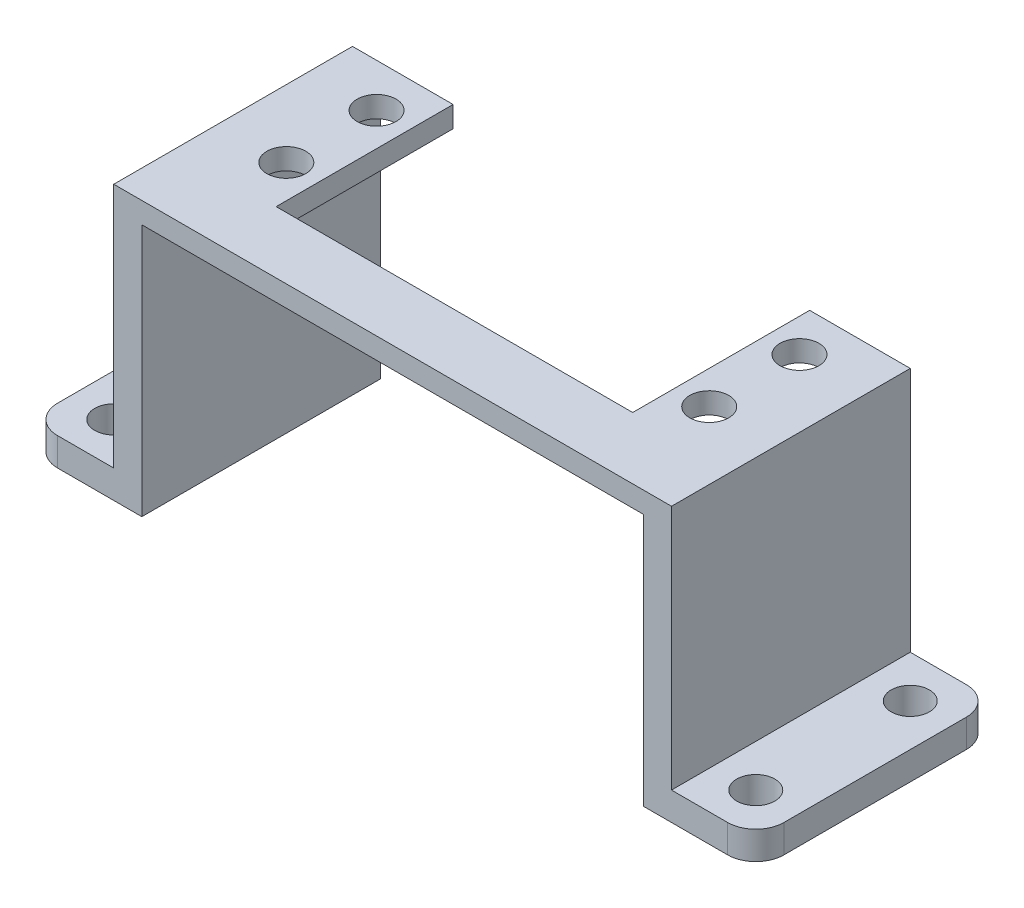
SolidWorks part; units mm, degrees
ref_plane "Front Plane" through (0, 0, 0) normal (0, 0, 1) x (1, 0, 0)
ref_plane "Top Plane" through (0, 0, 0) normal (0, 1, 0) x (1, 0, 0)
ref_plane "Right Plane" through (0, 0, 0) normal (1, 0, 0) x (0, 0, -1)
sketch "Sketch1" plane through (0, 0, 0) normal (0, 1, 0) x (1, 0, 0)
  line L0 (20.15, 0) -> (-20.15, 0)
  line L1 (-20.15, 0) -> (-20.15, 20)
  line L2 (-20.15, 20) -> (-31.52, 20)
  line L3 (-31.52, 20) -> (-31.52, -6.985)
  line L4 (-31.52, -6.985) -> (31.52, -6.985)
  line L5 (0, 0) -> (0, -6.985)
  line L6 (31.52, 20) -> (31.52, -6.985)
  line L7 (20.15, 20) -> (31.52, 20)
  line L8 (20.15, 0) -> (20.15, 20)
  circle A0 centre (-23.9, 15.1) radius 2.2
  circle A1 centre (-23.9, 4.9) radius 2.2
  circle A2 centre (23.9, 4.9) radius 2.2
  circle A3 centre (23.9, 15.1) radius 2.2
  point P0 (0, 0)
  dimension "D3" = 4.4
  dimension "D6" = 4.4
  dimension "D1" = 3.75
  dimension "D2" = 7.62
  dimension "D4" = 4.9
  dimension "D5" = 10.2
  dimension "D7" = 4.9
  dimension "D8" = 6.985
  dimension "D9" = 23.9
  dimension "D10" = 0
extrude "Boss-Extrude1" add sketch "Sketch1" along normal blind 2.3813
sketch "Sketch2" plane through (0, 0, 0) normal (0, -1, 0) x (1, 0, 0)
  line L0 (-31.52, 6.985) -> (31.52, 6.985) construction
  line L1 (31.52, -20) -> (28.345, -20)
  line L2 (31.52, -20) -> (31.52, 6.985)
  line L3 (31.52, 6.985) -> (28.345, 6.985)
  line L4 (28.345, -20) -> (28.345, 6.985)
  line L6 (-31.52, -20) -> (-28.345, -20)
  line L7 (-31.52, -20) -> (-31.52, 6.985)
  line L8 (-31.52, 6.985) -> (-28.345, 6.985)
  line L9 (-28.345, -20) -> (-28.345, 6.985)
  dimension "D1" = 3.175
  dimension "D2" = 3.175
extrude "Boss-Extrude2" add sketch "Sketch2" along normal blind 28.575
sketch "Sketch3" plane through (31.52, 0, 0) normal (1, 0, 0) x (0, 0, -1)
  line L0 (20, 2.3813) -> (20, -28.575) construction
  line L1 (-6.985, -28.575) -> (20, -28.575)
  line L2 (-6.985, -28.575) -> (-6.985, -25.4)
  line L3 (-6.985, -25.4) -> (20, -25.4)
  line L4 (20, -28.575) -> (20, -25.4)
  dimension "D1" = 3.175
extrude "Boss-Extrude3" add sketch "Sketch3" along normal blind 9.525
sketch "Sketch4" plane through (-31.52, 0, 0) normal (-1, 0, 0) x (0, 0, 1)
  line L0 (6.985, 2.3813) -> (6.985, -28.575) construction
  line L1 (-20, -28.575) -> (6.985, -28.575)
  line L2 (-20, -28.575) -> (-20, -25.4)
  line L3 (-20, -25.4) -> (6.985, -25.4)
  line L4 (6.985, -28.575) -> (6.985, -25.4)
  dimension "D1" = 3.175
extrude "Boss-Extrude4" add sketch "Sketch4" along normal blind 9.525
fillet "Fillet1" radius 3.175 4 edges at (-41.045, -26.9875, 6.985) (-41.045, -26.9875, -20) (41.045, -26.9875, 6.985) (41.045, -26.9875, -20)
sketch "Sketch5" plane through (0, -25.4, 0) normal (0, 1, 0) x (1, 0, 0)
  line L1 (41.045, 16.825) -> (41.045, -3.81) construction
  line L2 (37.87, -6.985) -> (31.52, -6.985) construction
  line L3 (37.87, 20) -> (31.52, 20) construction
  line L4 (-41.045, -3.81) -> (-41.045, 16.825) construction
  circle A0 centre (36.2825, -2.2225) radius 2.159
  circle A1 centre (36.2825, 15.2375) radius 2.159
  circle A2 centre (-36.2825, -2.2225) radius 2.159
  circle A3 centre (-36.2825, 15.2375) radius 2.159
  dimension "D1" = 4.318
  dimension "D2" = 4.318
  dimension "D3" = 4.318
  dimension "D4" = 4.318
  dimension "D5" = 4.7625
  dimension "D6" = 0
  dimension "D7" = 4.7625
  dimension "D8" = 4.7625
  dimension "D9" = 4.7625
  dimension "D10" = 0
  dimension "D11" = 0
  dimension "D12" = 0
extrude "Cut-Extrude1" cut sketch "Sketch5" against normal up to surface (3.175 mm away) up to face at (35.9725, -28.575, -6.5075)
